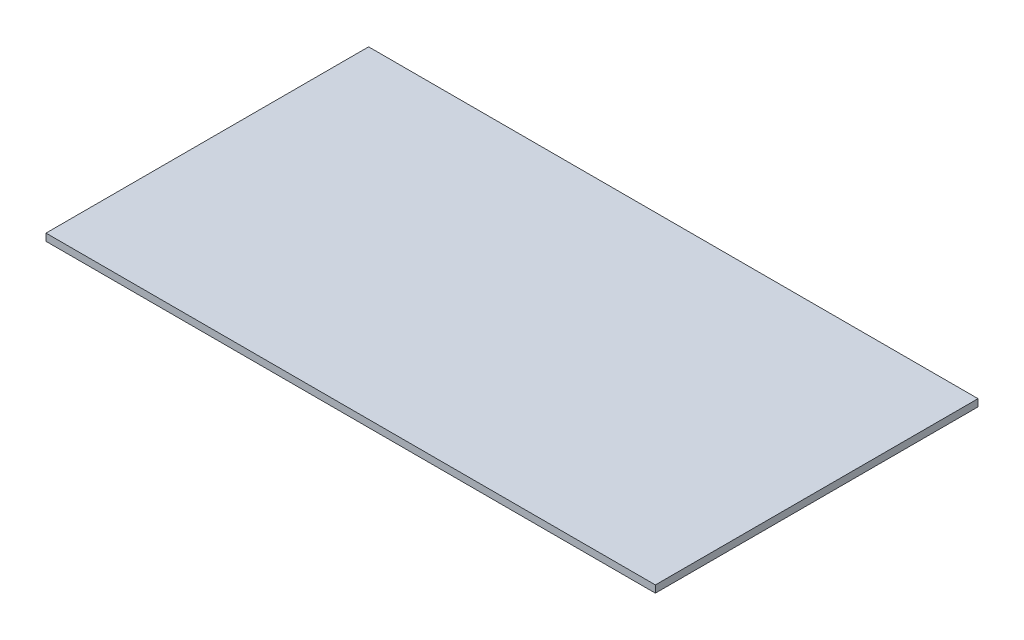
SolidWorks part; units mm, degrees
material "AISI 304"
ref_plane "Piano frontale" through (0, 0, 0) normal (0, 0, 1) x (1, 0, 0)
ref_plane "Piano superiore" through (0, 0, 0) normal (0, 1, 0) x (1, 0, 0)
ref_plane "Piano destro" through (0, 0, 0) normal (1, 0, 0) x (0, 0, -1)
sketch "Schizzo1" plane through (0, 0, 0) normal (0, 1, 0) x (1, 0, 0)
  line L1 (425, -225) -> (-425, -225)
  line L2 (425, -225) -> (425, 225)
  line L3 (425, 225) -> (-425, 225)
  line L4 (-425, -225) -> (-425, 225)
  line L5 (425, -225) -> (-425, 225) construction
  line L6 (425, 225) -> (-425, -225) construction
  point P0 (0, 0)
extrude "Estrusione-Estrusione1" add sketch "Schizzo1" along normal blind 10
